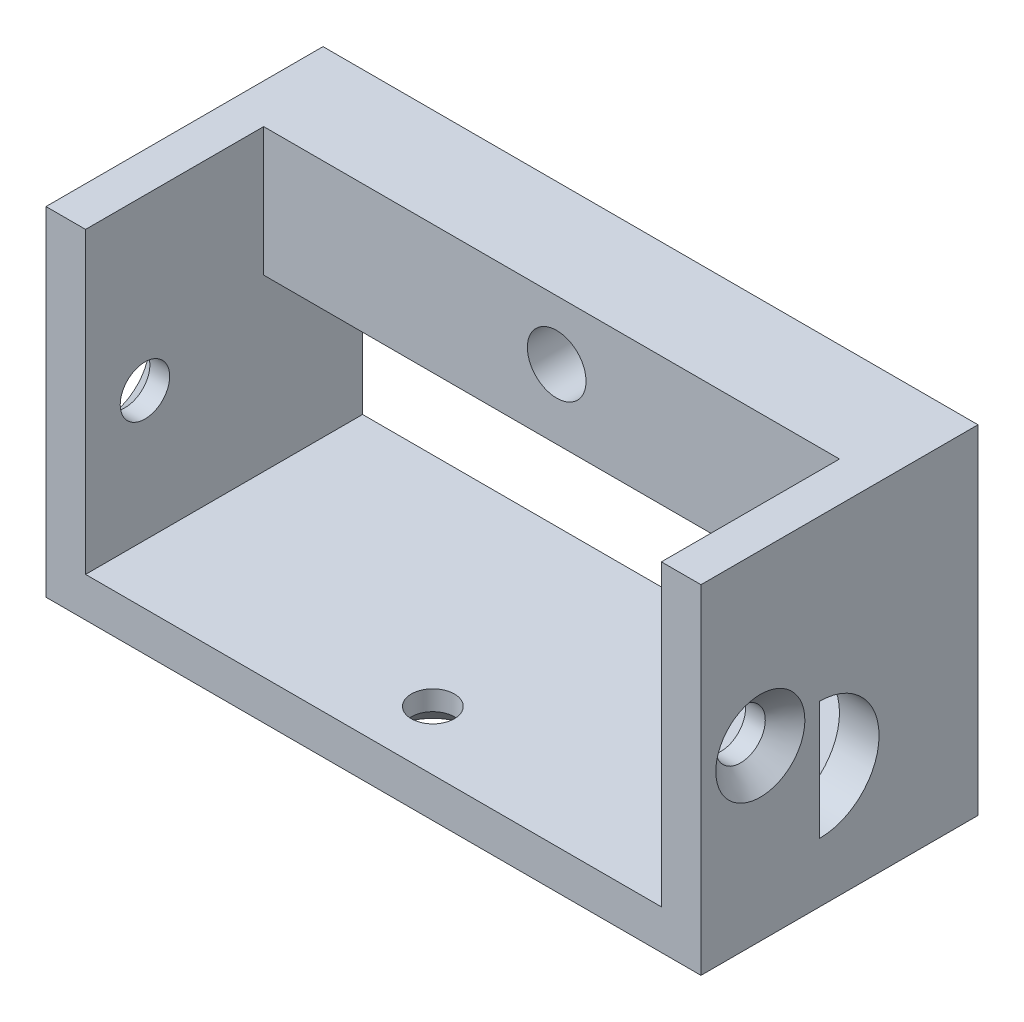
SolidWorks part; units mm, degrees
material "ABS"
ref_plane "Спереди" through (0, 0, 0) normal (0, 0, 1) x (1, 0, 0)
ref_plane "Сверху" through (0, 0, 0) normal (0, 1, 0) x (1, 0, 0)
ref_plane "Справа" through (0, 0, 0) normal (1, 0, 0) x (0, 0, -1)
sketch "Эскиз1" plane through (0, 0, 0) normal (0, 0, 1) x (1, 0, 0)
  line L1 (0, 0) -> (-29.1, 0)
  line L2 (0, 0) -> (0, 6.5)
  line L3 (0, 6.5) -> (-29.1, 6.5)
  line L4 (-29.1, 0) -> (-29.1, 6.5)
  dimension "D1" = 6.5
  dimension "D2" = 29.1
extrude "Бобышка-Вытянуть1" add sketch "Эскиз1" along normal blind 5
sketch "Эскиз2" plane through (0, 0, 0) normal (0, 0, -1) x (-1, 0, 0)
  line L0 (29.1, 0) -> (0, 0) construction
  line L1 (0, 6.5) -> (-2, 6.5)
  line L2 (0, 6.5) -> (0, -8.6)
  line L3 (0, -8.6) -> (-2, -8.6)
  line L4 (-2, 6.5) -> (-2, -8.6)
  line L5 (29.1, 6.5) -> (31.1, 6.5)
  line L6 (29.1, 6.5) -> (29.1, -8.6)
  line L7 (29.1, -8.6) -> (31.1, -8.6)
  line L8 (31.1, 6.5) -> (31.1, -8.6)
  line L9 (-2, -8.6) -> (31.1, -8.6)
  line L10 (-2, -8.6) -> (-2, -10.6)
  line L11 (-2, -10.6) -> (31.1, -10.6)
  line L12 (31.1, -8.6) -> (31.1, -10.6)
  line M9 (0, 6.5) -> (0, 0)
  line M11 (29.1, 0) -> (29.1, 6.5)
  dimension "D1" = 2
  dimension "D2" = 2
  dimension "D3" = 2
  dimension "D4" = 8.6
extrude "Бобышка-Вытянуть2" add sketch "Эскиз2" against normal blind 8 contours L12 L7 L9 L3 L10 L11 | L1 L4 L3 L2 M9 | L8 L5 L6 L7 M11
sketch "Эскиз3" plane through (2, 0, 0) normal (1, 0, 0) x (0, 0, -1)
  line L0 (-8, 6.5) -> (-8, -10.6) construction
  line L1 (-8, -8.6) -> (0, -8.6) construction
  circle A0 centre (-8, -4.6) radius 3
  dimension "D2" = 6
  dimension "D1" = 4
extrude "Вырез под провод" cut sketch "Эскиз3" against normal blind 3
sketch "Эскиз4" plane through (0, 0, 8) normal (0, 0, 1) x (1, 0, 0)
  line L0 (2, 6.5) -> (2, -10.6)
  line L1 (2, -10.6) -> (-31.1, -10.6)
  line L2 (-31.1, -10.6) -> (-31.1, 6.5)
  line L3 (-31.1, 6.5) -> (-29.1, 6.5)
  line L4 (-29.1, 6.5) -> (-29.1, -8.6)
  line L5 (-29.1, -8.6) -> (0, -8.6)
  line L6 (0, -8.6) -> (0, 6.5)
  line L7 (0, 6.5) -> (2, 6.5)
extrude "Юбка крепления" add sketch "Эскиз4" along normal blind 6
sketch "Эскиз5" plane through (2, 0, 0) normal (1, 0, 0) x (0, 0, -1)
  line L0 (-14, -10.6) -> (-14, 6.5) construction
  line L1 (0, -2.05) -> (-14, -2.05) construction
  line L2 (0, 6.5) -> (0, -10.6) construction
  circle A0 centre (-11, -2.05) radius 1.25
  dimension "D2" = 2.5
  dimension "D1" = 3
extrude "Вырез-Вытянуть2" cut sketch "Эскиз5" against normal through all
chamfer "Фаска1" distance 1 angle 45 2 edges at (-31.1, -0.8, 11) (2, -0.8, 11)
sketch "Эскиз6" plane through (0, -10.6, 0) normal (0, -1, 0) x (-1, 0, 0)
  line L0 (14.55, 0) -> (14.55, -14) construction
  line L1 (-2, 0) -> (31.1, 0) construction
  line L2 (31.1, -14) -> (-2, -14) construction
  circle A0 centre (14.55, -11) radius 1.0871
  dimension "D1" = 3
extrude "Вырез-Вытянуть3" cut sketch "Эскиз6" against normal blind 5
chamfer "Фаска2" distance 1 angle 45 1 edges at (-14.55, -10.6, 9.9129)
sketch "Эскиз7" plane through (0, 0, 0) normal (0, 0, -1) x (-1, 0, 0)
  line L0 (14.55, 6.5) -> (13.0726, -10.6) construction
  line L1 (-2, 6.5) -> (31.1, 6.5) construction
  line L2 (-2, -10.6) -> (31.1, -10.6) construction
  circle A0 centre (14.2908, 3.5) radius 1.4821
  dimension "D1" = 3
extrude "Вырез-Вытянуть4" cut sketch "Эскиз7" against normal blind 5
chamfer "Фаска3" distance 1 angle 45 1 edges at (-15.7729, 3.5, 0)
